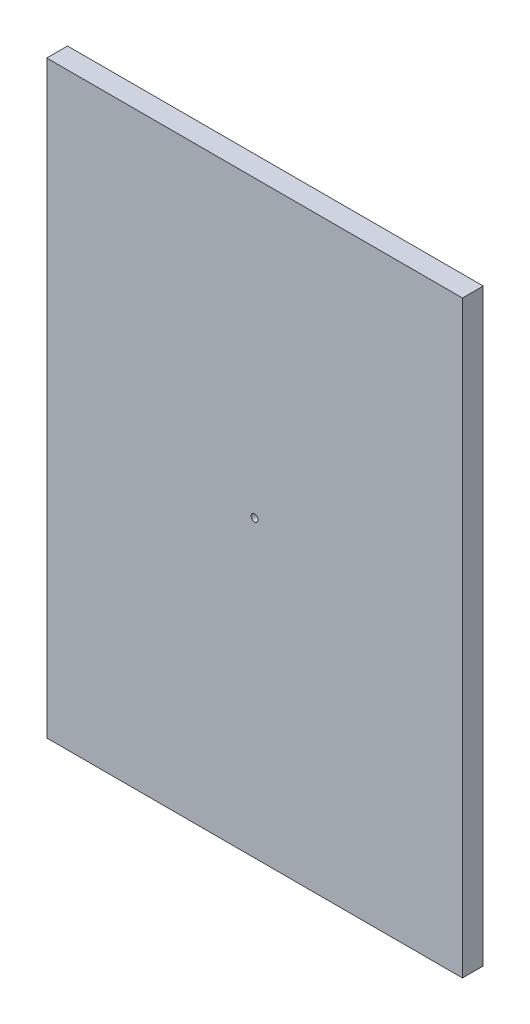
SolidWorks part; units mm, degrees
material "Glass"
ref_plane "Front Plane" through (0, 0, 0) normal (0, 0, 1) x (1, 0, 0)
ref_plane "Top Plane" through (0, 0, 0) normal (0, 1, 0) x (1, 0, 0)
ref_plane "Right Plane" through (0, 0, 0) normal (1, 0, 0) x (0, 0, -1)
sketch "Sketch1" plane through (0, 0, 0) normal (0, 0, 1) x (1, 0, 0)
  line L1 (0, 0) -> (60, 0)
  line L2 (0, 0) -> (0, -85)
  line L3 (0, -85) -> (60, -85)
  line L4 (60, 0) -> (60, -85)
  circle A0 centre (30, -42.5) radius 0.5
  point P7 (60, -42.5)
  point P8 (30, 0)
  dimension "D3" = 1
  dimension "D1" = 60
  dimension "D2" = 85
extrude "Boss-Extrude1" add sketch "Sketch1" along normal blind 3
ref_plane "Plane1" through (30, 0, 0) normal (1, 0, 0) x (0, 0, -1)
sketch "Sketch2" plane through (30, 0, 0) normal (1, 0, 0) x (0, 0, -1)
  line L1 (-3, -42.5) -> (-8, -42.5) construction
  line L2 (-3, -42.5) -> (-215.132, 169.632) construction
  line L4 (-3, 0) -> (-3, -85) construction
  dimension "D1" = 5
  dimension "D2" = 45
  dimension "D4" = 300
